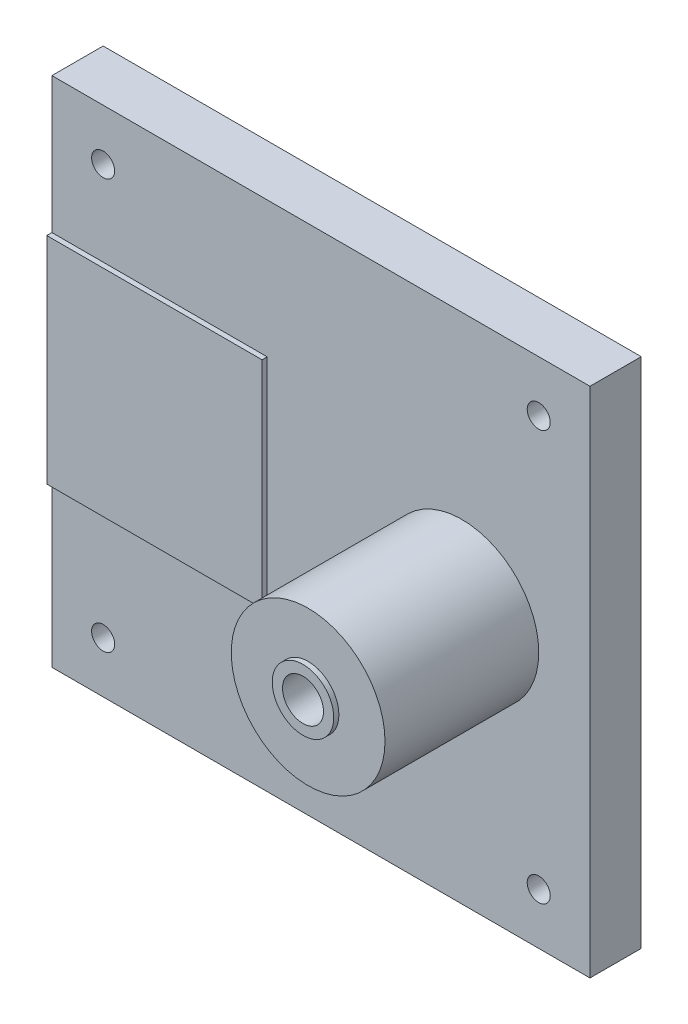
SolidWorks part; units mm, degrees
ref_plane "Front Plane" through (0, 0, 0) normal (0, 0, 1) x (1, 0, 0)
ref_plane "Top Plane" through (0, 0, 0) normal (0, 1, 0) x (1, 0, 0)
ref_plane "Right Plane" through (0, 0, 0) normal (1, 0, 0) x (0, 0, -1)
sketch "Sketch1" plane through (0, 0, 0) normal (0, 0, 1) x (1, 0, 0)
  line L1 (-80, 50) -> (25, 50)
  line L2 (-80, 50) -> (-80, -50)
  line L3 (-80, -50) -> (25, -50)
  line L4 (25, 50) -> (25, -50)
  dimension "D1" = 100
  dimension "D2" = 25
  dimension "D3" = 80
extrude "Boss-Extrude1" add sketch "Sketch1" along normal blind 10
sketch "Sketch2" plane through (0, 0, 10) normal (0, 0, 1) x (1, 0, 0)
  line L0 (25, 50) -> (-80, 50) construction
  line L1 (-27.5, 50) -> (-27.5, 30.3977) construction
  line L4 (-80, 50) -> (-80, -50) construction
  line L5 (0, 22.2969) -> (0, -13.2409) construction
  line L6 (-17.9747, 0) -> (19.2096, 0) construction
  circle A0 centre (-70, 40) radius 2.25
  circle A1 centre (15, -40) radius 2.25
  circle A2 centre (-70, -40) radius 2.25
  circle A3 centre (15, 40) radius 2.25
  dimension "D1" = 4.5
  dimension "D2" = 10
  dimension "D3" = 10
sketch "Sketch4" plane through (0, 0, 10) normal (0, 0, 1) x (1, 0, 0)
  circle A0 centre (0, 0) radius 15
  dimension "D1" = 30
extrude "Boss-Extrude2" add sketch "Sketch4" along normal blind 30
sketch "Sketch5" plane through (0, 0, 40) normal (0, 0, 1) x (1, 0, 0)
  circle A0 centre (0, 0) radius 4
  dimension "D1" = 8
extrude "Cut-Extrude3" cut sketch "Sketch5" against normal blind 30
sketch "Sketch6" plane through (0, 0, 10) normal (0, 0, 1) x (1, 0, 0)
  line L0 (-80, 50) -> (-80, -50) construction
  line L1 (-38, 23.4745) -> (-80, 23.4745)
  line L2 (-38, 23.4745) -> (-38, -18.5255)
  line L3 (-38, -18.5255) -> (-80, -18.5255)
  line L4 (-80, 23.4745) -> (-80, -18.5255)
  line L5 (-38, 23.4745) -> (-80, -18.5255) construction
  line L6 (-38, -18.5255) -> (-80, 23.4745) construction
  point P0 (-59, 2.4745)
  dimension "D1" = 42
  dimension "D2" = 42
  dimension "D3" = 0
extrude "Boss-Extrude3" add sketch "Sketch6" along normal blind 1
extrude "Cut-Extrude4" cut sketch "Sketch2" against normal through all
sketch "Local Files1" plane through (0, 0, 40) normal (0, 0, 1) x (1, 0, 0)
  circle A0 centre (0, 0) radius 4
  circle A1 centre (0, 0) radius 6
  dimension "D1" = 12
extrude "Boss-Extrude4" add sketch "Local Files1" along normal blind 1
